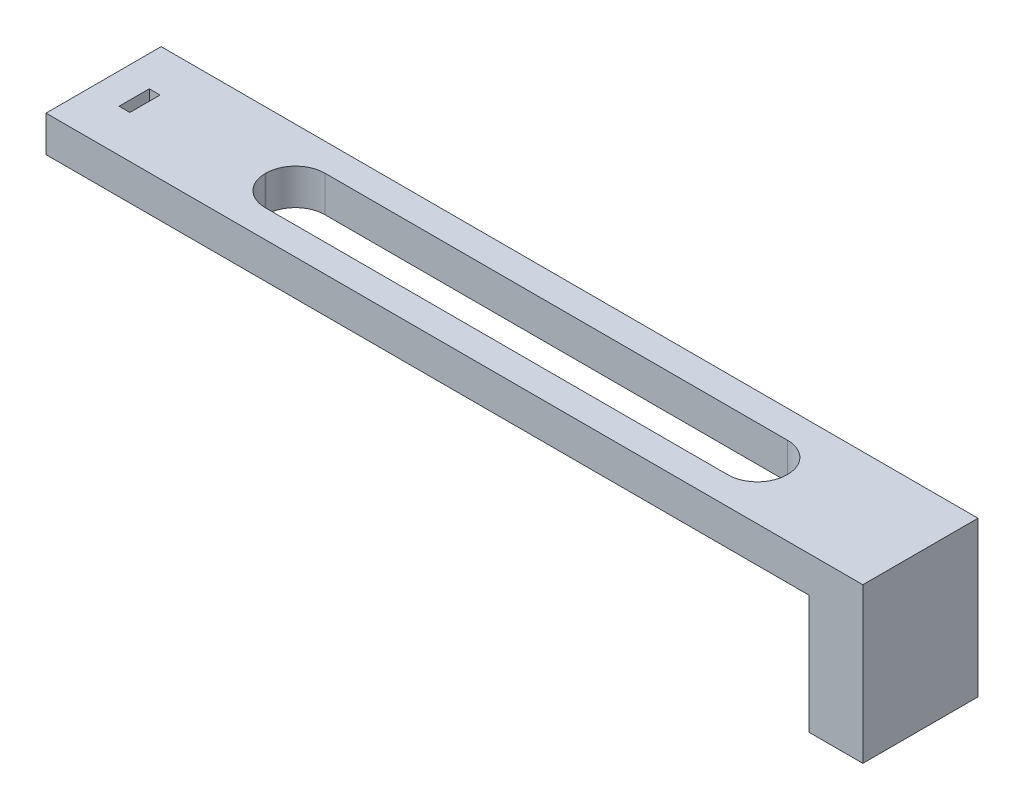
SolidWorks part; units mm, degrees
ref_plane "정면" through (0, 0, 0) normal (0, 0, 1) x (1, 0, 0)
ref_plane "윗면" through (0, 0, 0) normal (0, 1, 0) x (1, 0, 0)
ref_plane "우측면" through (0, 0, 0) normal (1, 0, 0) x (0, 0, -1)
sketch "스케치1" plane through (0, 0, 0) normal (0, 0, 1) x (1, 0, 0)
  line L0 (-106, 0) -> (0, 0)
  line L1 (0, 0) -> (0, -16.5)
  line L2 (0, -16.5) -> (7.5, -16.5)
  line L3 (7.5, -16.5) -> (7.5, 5)
  line L4 (7.5, 5) -> (-106, 5)
  line L5 (-106, 5) -> (-106, 0)
  dimension "D1" = 5
  dimension "D2" = 106
  dimension "D3" = 16.5
  dimension "D4" = 7.5
extrude "보스-돌출1" add sketch "스케치1" along normal blind 16
sketch "스케치2" plane through (0, 0, 0) normal (0, -1, 0) x (1, 0, 0)
  line L0 (-106, 16) -> (-106, 0) construction
  line L1 (-101.75, 10.1) -> (-100.25, 10.1)
  line L2 (-101.75, 10.1) -> (-101.75, 5.9)
  line L3 (-101.75, 5.9) -> (-100.25, 5.9)
  line L4 (-100.25, 10.1) -> (-100.25, 5.9)
  line L5 (-101.75, 10.1) -> (-100.25, 5.9) construction
  line L6 (-101.75, 5.9) -> (-100.25, 10.1) construction
  line L7 (7.5, 0) -> (-106, 0) construction
  line L9 (-106, 0) -> (0, 0) construction
  line L10 (-11, 3.85) -> (-83.5, 3.85)
  line L11 (-11, 3.85) -> (-11, 12.15)
  line L12 (-11, 12.15) -> (-83.5, 12.15)
  line L13 (-83.5, 3.85) -> (-83.5, 12.15)
  line L14 (-11, 3.85) -> (-83.5, 12.15) construction
  line L15 (-11, 12.15) -> (-83.5, 3.85) construction
  line L16 (0, 16) -> (0, 0) construction
  point P0 (-101, 8)
  point P8 (-47.25, 8)
  dimension "D1" = 4.25
  dimension "D2" = 1.5
  dimension "D3" = 8
  dimension "D4" = 4.2
  dimension "D5" = 8.3
  dimension "D6" = 8
  dimension "D7" = 16.75
  dimension "D8" = 11
extrude "컷-돌출1" cut sketch "스케치2" against normal through all
fillet "필렛1" radius 4.1 4 edges at (-11, 2.5, 3.85) (-11, 2.5, 12.15) (-83.5, 2.5, 3.85) (-83.5, 2.5, 12.15)
